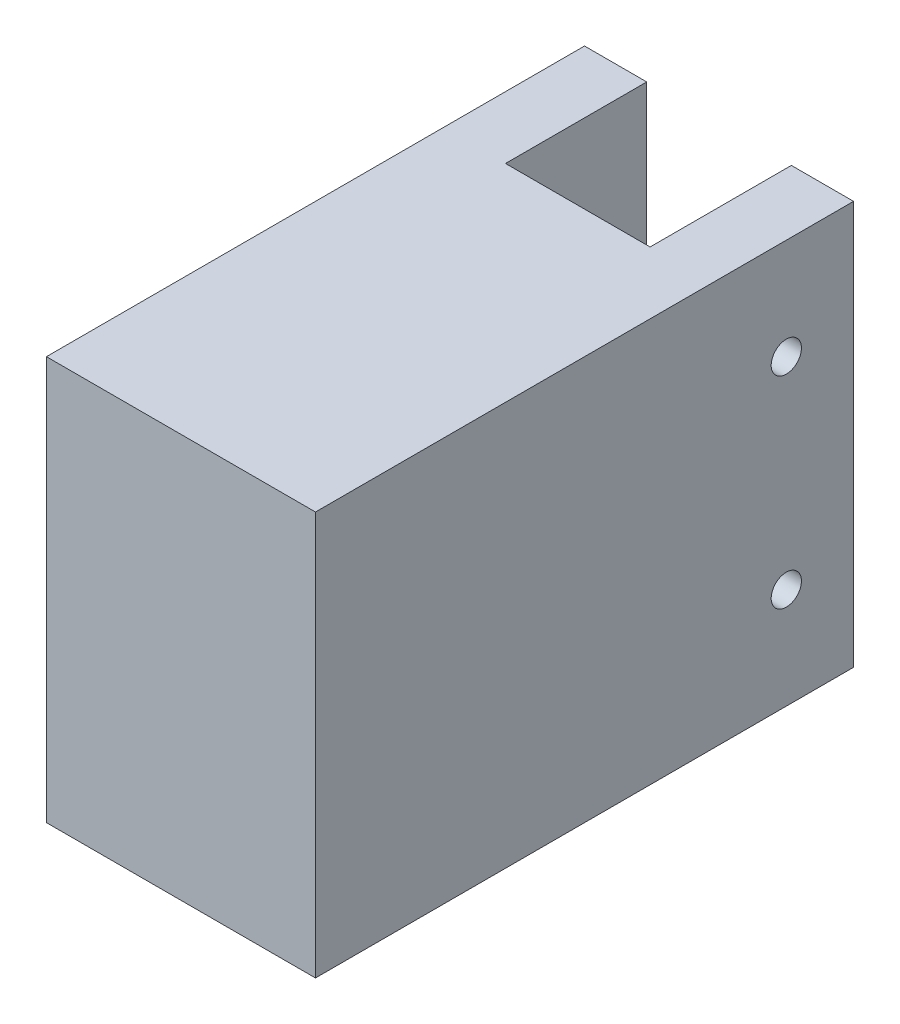
SolidWorks part; units mm, degrees
material "1060 Alloy"
ref_plane "Front Plane" through (0, 0, 0) normal (0, 0, 1) x (1, 0, 0)
ref_plane "Top Plane" through (0, 0, 0) normal (0, 1, 0) x (1, 0, 0)
ref_plane "Right Plane" through (0, 0, 0) normal (1, 0, 0) x (0, 0, -1)
sketch "Sketch1" plane through (0, 0, 0) normal (1, 0, 0) x (0, 0, -1)
  line L1 (30, -30) -> (-30, -30)
  line L2 (30, -30) -> (30, 30)
  line L3 (30, 30) -> (-30, 30)
  line L4 (-30, -30) -> (-30, 30)
  line L5 (30, -30) -> (-30, 30) construction
  line L6 (30, 30) -> (-30, -30) construction
  circle A0 centre (0, 0) radius 17.65
  point P0 (0, 0)
  dimension "D3" = 35.3
  dimension "D1" = 60
  dimension "D2" = 60
extrude "Boss-Extrude1" add sketch "Sketch1" along normal blind 40
sketch "Sketch2" plane through (0, 0, 30) normal (0, 0, 1) x (1, 0, 0)
  line L0 (40, 30) -> (0, 30) construction
  line L1 (10, 30) -> (30, 30)
  line L2 (10, 30) -> (10, 10)
  line L3 (10, 10) -> (30, 10)
  line L4 (30, 30) -> (30, 10)
  point P8 (20, 30)
  point P9 (20, 10)
  dimension "D1" = 20
  dimension "D2" = 20
sketch "Sketch3" plane through (0, 0, 0) normal (-1, 0, 0) x (0, 0, 1)
  line L4 (30, -30) -> (30, 30)
  line L5 (30, 30) -> (-30, 30)
  line L6 (-30, 30) -> (-30, -30)
  line L7 (-30, -30) -> (30, -30)
  line L8 (30, -30) -> (30, 30)
  line L9 (30, 30) -> (-30, 30)
  line L10 (-30, 30) -> (-30, -30)
  line L11 (-30, -30) -> (30, -30)
  dimension "D1" = 0
sketch "Sketch4" plane through (0, 0, -30) normal (0, 0, -1) x (-1, 0, 0)
  line L0 (-40, -30) -> (0, -30) construction
  line L1 (-40, 30) -> (-30, 30)
  line L2 (-40, 30) -> (-40, -30)
  line L3 (-40, -30) -> (-30, -30)
  line L4 (-30, 30) -> (-30, -30)
  dimension "D1" = 10
extrude "Boss-Extrude2" add sketch "Sketch4" along normal blind 20
sketch "Sketch5" plane through (40, 0, 0) normal (1, 0, 0) x (0, 0, -1)
  line L0 (0, 0) -> (75.5844, 0) construction
  line L1 (-30, -30) -> (50, -30) construction
  line L2 (50, 30) -> (50, -30) construction
  circle A0 centre (40, -15) radius 2.25
  circle A1 centre (40, 15) radius 2.25
  dimension "D1" = 4.5
  dimension "D2" = 15
  dimension "D3" = 10
extrude "Cut-Extrude1" cut sketch "Sketch5" against normal through all
ref_plane "Plane1" through (20, 0, 0) normal (1, 0, 0) x (0, 0, -1)
mirror "Mirror1" about plane through (20, 0, 0) normal (1, 0, 0) of "Cut-Extrude1", "Boss-Extrude2"
sketch "Sketch6" plane through (40, 0, 0) normal (1, 0, 0) x (0, 0, -1)
  circle A0 centre (0, 0) radius 17.65 construction
  circle A1 centre (0, 0) radius 17.65
extrude "Boss-Extrude3" add sketch "Sketch6" against normal blind 15
sketch "Sketch7" plane through (0, 30, 0) normal (0, 1, 0) x (1, 0, 0)
  line L0 (10, 50) -> (0, 50) construction
  line L1 (9.25, 50) -> (30.75, 50)
  line L2 (9.25, 50) -> (9.25, 29)
  line L3 (9.25, 29) -> (30.75, 29)
  line L4 (30.75, 50) -> (30.75, 29)
  line L5 (20, -33) -> (20, 33) construction
  point P6 (20, 29)
  dimension "D1" = 21.5
  dimension "D2" = 21
extrude "Cut-Extrude2" cut sketch "Sketch7" against normal through all
sketch "Sketch8" plane through (0, 0, 0) normal (-1, 0, 0) x (0, 0, 1)
  circle A0 centre (0, 0) radius 18.5
  dimension "D1" = 37
extrude "Cut-Extrude3" [suppressed] cut sketch "Sketch8" against normal blind 10
